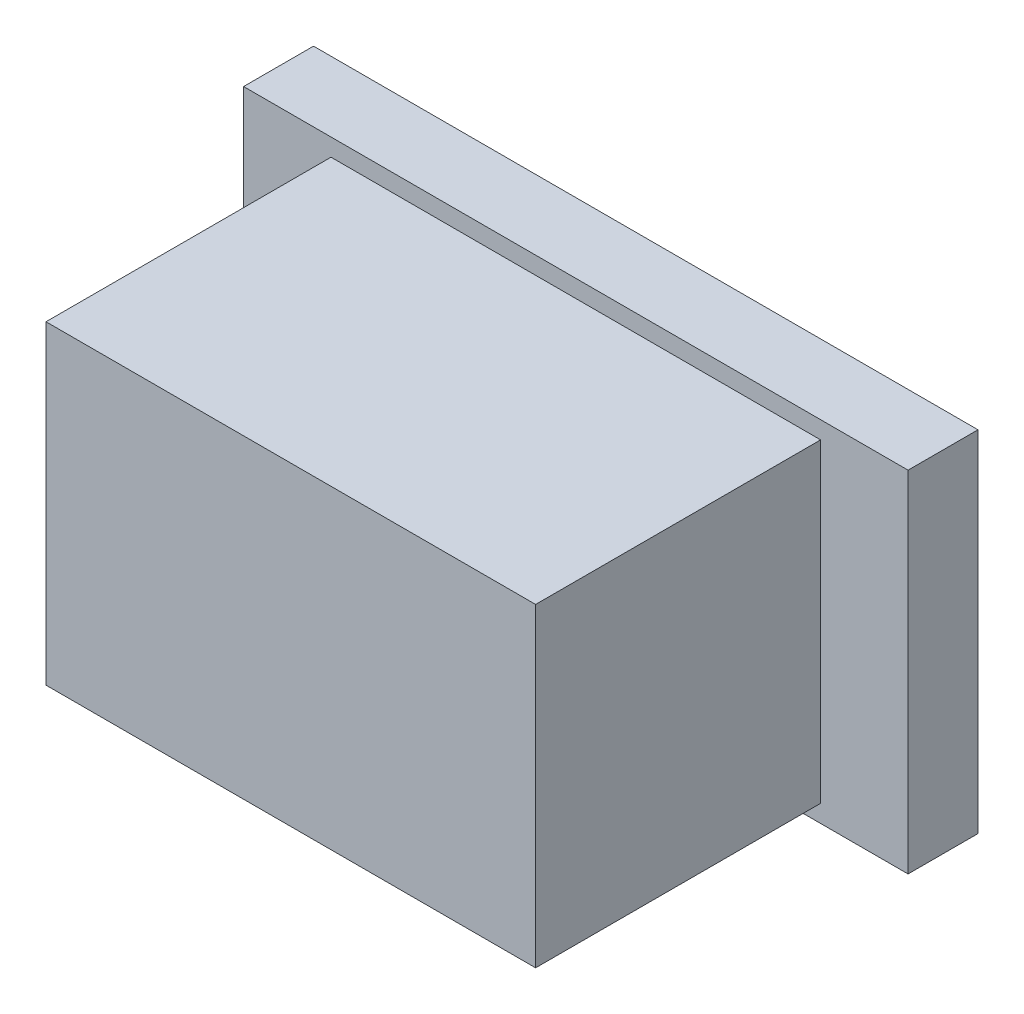
SolidWorks part; units mm, degrees
ref_plane "前基準面" through (0, 0, 0) normal (0, 0, 1) x (1, 0, 0)
ref_plane "上基準面" through (0, 0, 0) normal (0, 1, 0) x (1, 0, 0)
ref_plane "右基準面" through (0, 0, 0) normal (1, 0, 0) x (0, 0, -1)
sketch "草圖1" plane through (0, 0, 0) normal (0, 0, 1) x (1, 0, 0)
  line L0 (-3.8, -2) -> (3.8, -2)
  line L1 (3.8, -2) -> (3.8, 2)
  line L2 (3.8, 2) -> (-3.8, 2)
  line L3 (-3.8, 2) -> (-3.8, -2)
extrude "flange" add sketch "草圖1" along normal blind 0.8
sketch "草圖2" plane through (0, 0, 0) normal (0, 0, 1) x (1, 0, 0)
  line L0 (-2.8, -1.8) -> (2.8, -1.8)
  line L1 (2.8, -1.8) -> (2.8, 1.8)
  line L2 (2.8, 1.8) -> (-2.8, 1.8)
  line L3 (-2.8, 1.8) -> (-2.8, -1.8)
extrude "head" add sketch "草圖2" along normal blind 4.06
